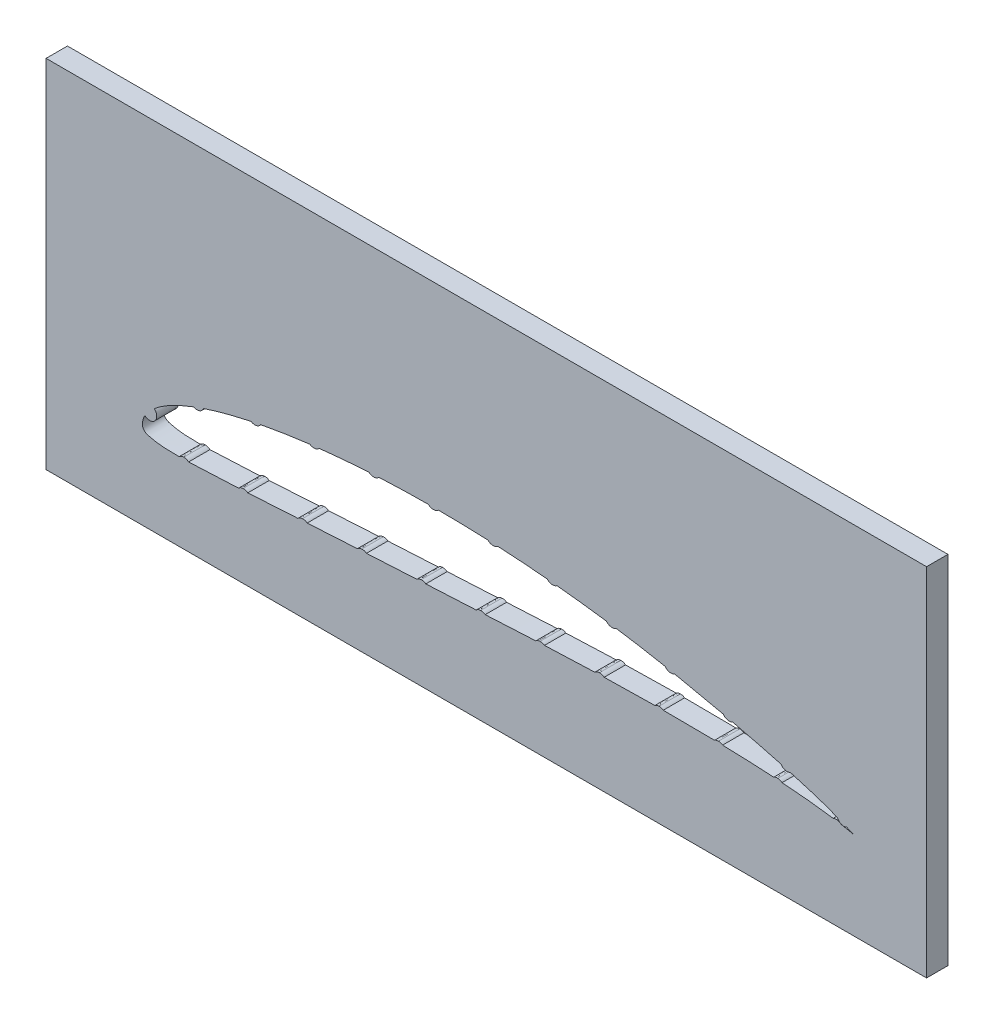
SolidWorks part; units mm, degrees
ref_plane "Front Plane" through (0, 0, 0) normal (0, 0, 1) x (1, 0, 0)
ref_plane "Top Plane" through (0, 0, 0) normal (0, 1, 0) x (1, 0, 0)
ref_plane "Right Plane" through (0, 0, 0) normal (1, 0, 0) x (0, 0, -1)
sketch "Sketch1" plane through (0, 0, 0) normal (0, 0, 1) x (1, 0, 0)
  line L0 (156.4732, 37.7124) -> (156.4732, -12.2876)
  line L4 (-29.9383, -12.2876) -> (280.0617, -12.2876)
  line L5 (280.0617, -12.2876) -> (280.0617, 37.7124)
  line L6 (280.0617, 37.7124) -> (-29.9383, 37.7124)
  line L7 (-29.9383, 37.7124) -> (-29.9383, -12.2876)
  line L8 (156.4732, -12.2876) -> (280.0617, -12.2876)
  line L9 (280.0617, -12.2876) -> (280.0617, 37.7124)
  line L10 (280.0617, 37.7124) -> (156.4732, 37.7124)
  spline S1 degree 3 poles (270, 0) (270.0005, 0.0034) (269.6048, 0.1306) (269.2247, 0.2963) (268.3309, 0.6499) (267.2772, 1.0813) (265.9343, 1.5924) (264.3561, 2.1312) (262.5223, 2.6908) (260.4482, 3.2815) (258.1458, 3.9019) (255.6342, 4.5431) (252.9328, 5.1985) (250.0623, 5.8584) (247.0442, 6.5136) (243.9006, 7.1514) (240.651, 7.7602) (237.3071, 8.3135) (233.8836, 8.807) (230.3953, 9.2406) (226.8572, 9.6022) (223.2866, 9.8965) (219.7002, 10.1178) (216.117, 10.2616) (212.5548, 10.3343) (209.0315, 10.3285) (205.5651, 10.2474) (202.1735, 10.094) (198.8746, 9.8685) (195.6857, 9.5758) (192.6237, 9.2175) (189.7053, 8.7967) (186.9453, 8.3202) (184.3583, 7.7892) (181.9576, 7.2105) (179.7548, 6.5902) (177.7618, 5.9318) (175.9857, 5.2473) (174.4355, 4.5345) (173.1182, 3.7996) (172.0268, 3.0646) (171.1713, 2.319) (170.5478, 1.59) (170.1375, 0.8847) (169.9896, 0.2277) (169.9947, -0.3832) (170.4334, -0.8626) (171.1821, -1.0599) (172.1855, -1.2647) (173.5199, -1.3596) (175.163, -1.3823) (177.125, -1.339) (179.3957, -1.2448) (181.9613, -1.1128) (184.8021, -0.9519) (187.8972, -0.7672) (191.2241, -0.5673) (194.7581, -0.3561) (198.4734, -0.1401) (202.3426, 0.0777) (206.3373, 0.2939) (210.4289, 0.5065) (214.5903, 0.72) (218.7992, 0.9415) (223.0374, 1.1621) (227.2837, 1.3719) (231.5085, 1.546) (235.6748, 1.6727) (239.7446, 1.7558) (243.6833, 1.7923) (247.4579, 1.7809) (251.0357, 1.7222) (254.3847, 1.6178) (257.4746, 1.4721) (260.2752, 1.2906) (262.7627, 1.0808) (264.9033, 0.8557) (266.6996, 0.6178) (268.0551, 0.4013) (269.1365, 0.1814) (269.5781, 0.1033) (269.9995, -0.0034) (270, 0) (270.0005, 0.0034) (269.6048, 0.1306) knots -0.000989 0 0 0 0.000979 0.003786 0.008179 0.01394 0.020915 0.029057 0.038414 0.048974 0.060645 0.073334 0.086939 0.101355 0.116471 0.132171 0.148332 0.16489 0.181807 0.198987 0.216369 0.233891 0.251455 0.26899 0.28641 0.303633 0.320589 0.337187 0.353353 0.369012 0.384083 0.3985 0.412191 0.425098 0.437171 0.448351 0.458606 0.467901 0.476216 0.483573 0.48997 0.495456 0.500132 0.503992 0.50723 0.509987 0.512501 0.516074 0.521095 0.527571 0.535587 0.545177 0.556302 0.568875 0.5828 0.597975 0.614286 0.631613 0.649826 0.668792 0.688371 0.708417 0.728797 0.749399 0.770146 0.790953 0.811664 0.832074 0.851999 0.871282 0.889761 0.90728 0.923686 0.938833 0.952579 0.964796 0.975365 0.984179 0.991107 0.996049 0.999011 1 1 1 1.000979 1.003786 1.008179 only from (270, 0) to (270, 0)
  spline S2 degree 3 poles (270, 0) (270.0005, 0.0034) (269.6048, 0.1306) (269.2247, 0.2963) (268.3309, 0.6499) (267.2772, 1.0813) (265.9343, 1.5924) (264.3561, 2.1312) (262.5223, 2.6908) (260.4482, 3.2815) (258.1458, 3.9019) (255.6342, 4.5431) (252.9328, 5.1985) (250.0623, 5.8584) (247.0442, 6.5136) (243.9006, 7.1514) (240.651, 7.7602) (237.3071, 8.3135) (233.8836, 8.807) (230.3953, 9.2406) (226.8572, 9.6022) (223.2866, 9.8965) (219.7002, 10.1178) (216.117, 10.2616) (212.5548, 10.3343) (209.0315, 10.3285) (205.5651, 10.2474) (202.1735, 10.094) (198.8746, 9.8685) (195.6857, 9.5758) (192.6237, 9.2175) (189.7053, 8.7967) (186.9453, 8.3202) (184.3583, 7.7892) (181.9576, 7.2105) (179.7548, 6.5902) (177.7618, 5.9318) (175.9857, 5.2473) (174.4355, 4.5345) (173.1182, 3.7996) (172.0268, 3.0646) (171.1713, 2.319) (170.5478, 1.59) (170.1375, 0.8847) (169.9896, 0.2277) (169.9947, -0.3832) (170.4334, -0.8626) (171.1821, -1.0599) (172.1855, -1.2647) (173.5199, -1.3596) (175.163, -1.3823) (177.125, -1.339) (179.3957, -1.2448) (181.9613, -1.1128) (184.8021, -0.9519) (187.8972, -0.7672) (191.2241, -0.5673) (194.7581, -0.3561) (198.4734, -0.1401) (202.3426, 0.0777) (206.3373, 0.2939) (210.4289, 0.5065) (214.5903, 0.72) (218.7992, 0.9415) (223.0374, 1.1621) (227.2837, 1.3719) (231.5085, 1.546) (235.6748, 1.6727) (239.7446, 1.7558) (243.6833, 1.7923) (247.4579, 1.7809) (251.0357, 1.7222) (254.3847, 1.6178) (257.4746, 1.4721) (260.2752, 1.2906) (262.7627, 1.0808) (264.9033, 0.8557) (266.6996, 0.6178) (268.0551, 0.4013) (269.1365, 0.1814) (269.5781, 0.1033) (269.9995, -0.0034) (270, 0) (270.0005, 0.0034) (269.6048, 0.1306) knots -0.000989 0 0 0 0.000979 0.003786 0.008179 0.01394 0.020915 0.029057 0.038414 0.048974 0.060645 0.073334 0.086939 0.101355 0.116471 0.132171 0.148332 0.16489 0.181807 0.198987 0.216369 0.233891 0.251455 0.26899 0.28641 0.303633 0.320589 0.337187 0.353353 0.369012 0.384083 0.3985 0.412191 0.425098 0.437171 0.448351 0.458606 0.467901 0.476216 0.483573 0.48997 0.495456 0.500132 0.503992 0.50723 0.509987 0.512501 0.516074 0.521095 0.527571 0.535587 0.545177 0.556302 0.568875 0.5828 0.597975 0.614286 0.631613 0.649826 0.668792 0.688371 0.708417 0.728797 0.749399 0.770146 0.790953 0.811664 0.832074 0.851999 0.871282 0.889761 0.90728 0.923686 0.938833 0.952579 0.964796 0.975365 0.984179 0.991107 0.996049 0.999011 1 1 1 1.000979 1.003786 1.008179 only from (270, 0) to (270, 0)
  dimension "D1" = 0
  dimension "D2" = 0
extrude "Boss-Extrude2" add sketch "Sketch1" along normal blind 3
sketch "Sketch3" plane through (0, 0, 3) normal (0, 0, 1) x (1, 0, 0)
  spline S0 degree 3 poles (270, 0) (270.0005, 0.0034) (269.6048, 0.1306) (269.2247, 0.2963) (268.3309, 0.6499) (267.2772, 1.0813) (265.9343, 1.5924) (264.3561, 2.1312) (262.5223, 2.6908) (260.4482, 3.2815) (258.1458, 3.9019) (255.6342, 4.5431) (252.9328, 5.1985) (250.0623, 5.8584) (247.0442, 6.5136) (243.9006, 7.1514) (240.651, 7.7602) (237.3071, 8.3135) (233.8836, 8.807) (230.3953, 9.2406) (226.8572, 9.6022) (223.2866, 9.8965) (219.7002, 10.1178) (216.117, 10.2616) (212.5548, 10.3343) (209.0315, 10.3285) (205.5651, 10.2474) (202.1735, 10.094) (198.8746, 9.8685) (195.6857, 9.5758) (192.6237, 9.2175) (189.7053, 8.7967) (186.9453, 8.3202) (184.3583, 7.7892) (181.9576, 7.2105) (179.7548, 6.5902) (177.7618, 5.9318) (175.9857, 5.2473) (174.4355, 4.5345) (173.1182, 3.7996) (172.0268, 3.0646) (171.1713, 2.319) (170.5478, 1.59) (170.1375, 0.8847) (169.9896, 0.2277) (169.9947, -0.3832) (170.4334, -0.8626) (171.1821, -1.0599) (172.1855, -1.2647) (173.5199, -1.3596) (175.163, -1.3823) (177.125, -1.339) (179.3957, -1.2448) (181.9613, -1.1128) (184.8021, -0.9519) (187.8972, -0.7672) (191.2241, -0.5673) (194.7581, -0.3561) (198.4734, -0.1401) (202.3426, 0.0777) (206.3373, 0.2939) (210.4289, 0.5065) (214.5903, 0.72) (218.7992, 0.9415) (223.0374, 1.1621) (227.2837, 1.3719) (231.5085, 1.546) (235.6748, 1.6727) (239.7446, 1.7558) (243.6833, 1.7923) (247.4579, 1.7809) (251.0357, 1.7222) (254.3847, 1.6178) (257.4746, 1.4721) (260.2752, 1.2906) (262.7627, 1.0808) (264.9033, 0.8557) (266.6996, 0.6178) (268.0551, 0.4013) (269.1365, 0.1814) (269.5781, 0.1033) (269.9995, -0.0034) (270, 0) (270.0005, 0.0034) (269.6048, 0.1306) knots -0.000989 0 0 0 0.000979 0.003786 0.008179 0.01394 0.020915 0.029057 0.038414 0.048974 0.060645 0.073334 0.086939 0.101355 0.116471 0.132171 0.148332 0.16489 0.181807 0.198987 0.216369 0.233891 0.251455 0.26899 0.28641 0.303633 0.320589 0.337187 0.353353 0.369012 0.384083 0.3985 0.412191 0.425098 0.437171 0.448351 0.458606 0.467901 0.476216 0.483573 0.48997 0.495456 0.500132 0.503992 0.50723 0.509987 0.512501 0.516074 0.521095 0.527571 0.535587 0.545177 0.556302 0.568875 0.5828 0.597975 0.614286 0.631613 0.649826 0.668792 0.688371 0.708417 0.728797 0.749399 0.770146 0.790953 0.811664 0.832074 0.851999 0.871282 0.889761 0.90728 0.923686 0.938833 0.952579 0.964796 0.975365 0.984179 0.991107 0.996049 0.999011 1 1 1 1.000979 1.003786 1.008179 only from (270, 0) to (270, 0) construction
  spline S1 degree 3 poles (270, 0) (270.0005, 0.0034) (269.6048, 0.1306) (269.2247, 0.2963) (268.3309, 0.6499) (267.2772, 1.0813) (265.9343, 1.5924) (264.3561, 2.1312) (262.5223, 2.6908) (260.4482, 3.2815) (258.1458, 3.9019) (255.6342, 4.5431) (252.9328, 5.1985) (250.0623, 5.8584) (247.0442, 6.5136) (243.9006, 7.1514) (240.651, 7.7602) (237.3071, 8.3135) (233.8836, 8.807) (230.3953, 9.2406) (226.8572, 9.6022) (223.2866, 9.8965) (219.7002, 10.1178) (216.117, 10.2616) (212.5548, 10.3343) (209.0315, 10.3285) (205.5651, 10.2474) (202.1735, 10.094) (198.8746, 9.8685) (195.6857, 9.5758) (192.6237, 9.2175) (189.7053, 8.7967) (186.9453, 8.3202) (184.3583, 7.7892) (181.9576, 7.2105) (179.7548, 6.5902) (177.7618, 5.9318) (175.9857, 5.2473) (174.4355, 4.5345) (173.1182, 3.7996) (172.0268, 3.0646) (171.1713, 2.319) (170.5478, 1.59) (170.1375, 0.8847) (169.9896, 0.2277) (169.9947, -0.3832) (170.4334, -0.8626) (171.1821, -1.0599) (172.1855, -1.2647) (173.5199, -1.3596) (175.163, -1.3823) (177.125, -1.339) (179.3957, -1.2448) (181.9613, -1.1128) (184.8021, -0.9519) (187.8972, -0.7672) (191.2241, -0.5673) (194.7581, -0.3561) (198.4734, -0.1401) (202.3426, 0.0777) (206.3373, 0.2939) (210.4289, 0.5065) (214.5903, 0.72) (218.7992, 0.9415) (223.0374, 1.1621) (227.2837, 1.3719) (231.5085, 1.546) (235.6748, 1.6727) (239.7446, 1.7558) (243.6833, 1.7923) (247.4579, 1.7809) (251.0357, 1.7222) (254.3847, 1.6178) (257.4746, 1.4721) (260.2752, 1.2906) (262.7627, 1.0808) (264.9033, 0.8557) (266.6996, 0.6178) (268.0551, 0.4013) (269.1365, 0.1814) (269.5781, 0.1033) (269.9995, -0.0034) (270, 0) (270.0005, 0.0034) (269.6048, 0.1306) knots -0.000989 0 0 0 0.000979 0.003786 0.008179 0.01394 0.020915 0.029057 0.038414 0.048974 0.060645 0.073334 0.086939 0.101355 0.116471 0.132171 0.148332 0.16489 0.181807 0.198987 0.216369 0.233891 0.251455 0.26899 0.28641 0.303633 0.320589 0.337187 0.353353 0.369012 0.384083 0.3985 0.412191 0.425098 0.437171 0.448351 0.458606 0.467901 0.476216 0.483573 0.48997 0.495456 0.500132 0.503992 0.50723 0.509987 0.512501 0.516074 0.521095 0.527571 0.535587 0.545177 0.556302 0.568875 0.5828 0.597975 0.614286 0.631613 0.649826 0.668792 0.688371 0.708417 0.728797 0.749399 0.770146 0.790953 0.811664 0.832074 0.851999 0.871282 0.889761 0.90728 0.923686 0.938833 0.952579 0.964796 0.975365 0.984179 0.991107 0.996049 0.999011 1 1 1 1.000979 1.003786 1.008179 only from (270, 0) to (270, 0) construction
  text T0 ".........................\r\n" font "Century Gothic" height 12
extrude "Boss-Extrude3" add sketch "Sketch3" against normal blind 3
sketch "Sketch4" plane through (0, 0, 3) normal (0, 0, 1) x (1, 0, 0)
  line L0 (239.794, 21.9257) -> (260.2877, 21.9257)
  line L1 (260.2877, 21.9257) -> (250.0409, 28.2357)
  line L2 (250.0409, 28.2357) -> (260.2877, 21.9257)
  line L3 (260.2877, 21.9257) -> (252.0193, 13.6572)
